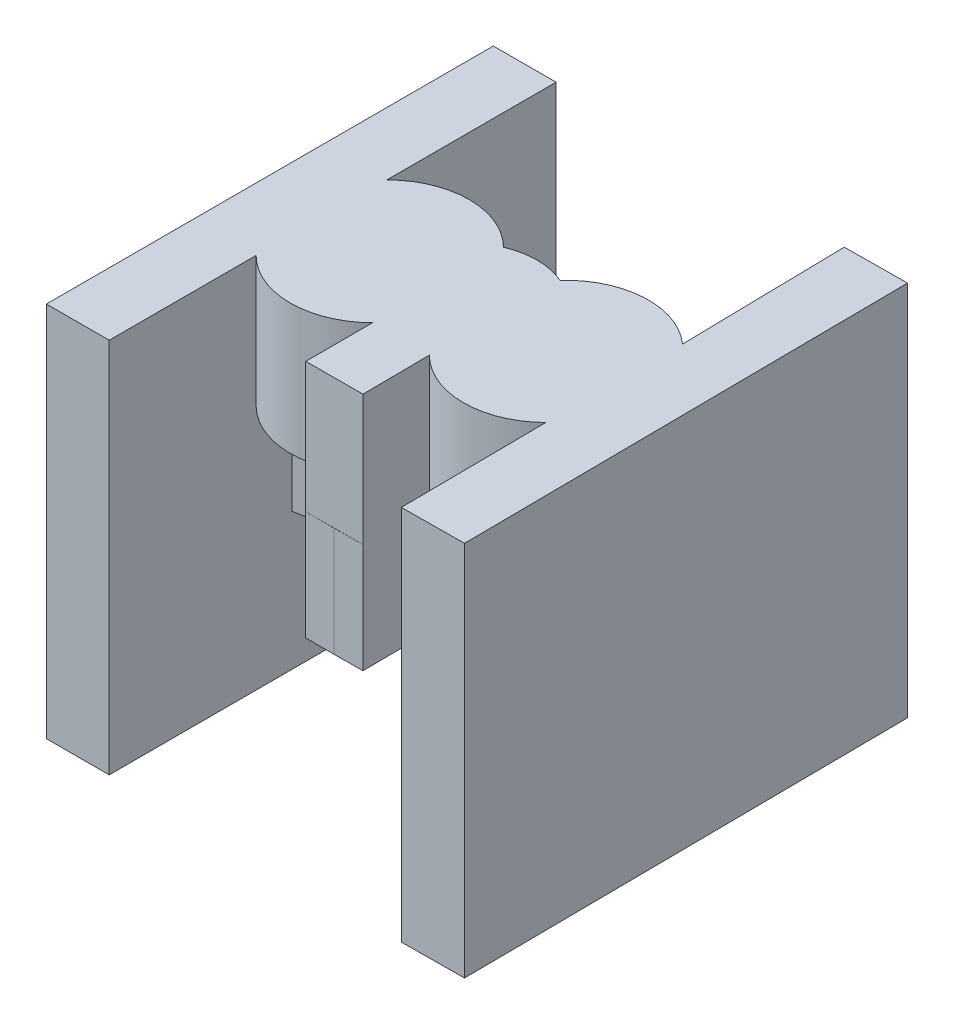
SolidWorks part; units mm, degrees
ref_plane "Front Plane" through (0, 0, 0) normal (0, 0, 1) x (1, 0, 0)
ref_plane "Top Plane" through (0, 0, 0) normal (0, 1, 0) x (1, 0, 0)
ref_plane "Right Plane" through (0, 0, 0) normal (1, 0, 0) x (0, 0, -1)
sketch "Sketch1" plane through (0, 0, 0) normal (0, 1, 0) x (1, 0, 0)
  line L0 (118.5, 375) -> (592.5, 375) construction
  line L1 (27.997, 26.1044) -> (30.497, 26.1044)
  line L2 (32.9969, 26.126) -> (30.497, 26.1044)
  line L3 (32.9969, 26.126) -> (32.9463, 31.9923)
  line L4 (43.0882, 40.7909) -> (40.3953, 39.9592)
  line L5 (42.9365, 58.3777) -> (43.0882, 40.7909)
  line L6 (48.4363, 58.4251) -> (42.9365, 58.3777)
  line L7 (48.7742, 19.251) -> (48.4363, 58.4251)
  line L8 (43.2744, 19.2036) -> (48.7742, 19.251)
  line L9 (43.1362, 35.2238) -> (43.2744, 19.2036)
  line L10 (40.4315, 35.7538) -> (43.1362, 35.2238)
  line L11 (24.9791, 40.7283) -> (20.4796, 39.8733)
  line L12 (25.0572, 34.5446) -> (20.4796, 35.6677)
  line L13 (20.4796, 35.6677) -> (17.7796, 35.1144)
  line L14 (17.7796, 35.1144) -> (17.7796, 19.0937)
  line L15 (17.7796, 19.0937) -> (12.2796, 19.0937)
  line L16 (12.2796, 19.0937) -> (12.2796, 58.2692)
  line L17 (12.2796, 58.2692) -> (17.7796, 58.2692)
  line L18 (17.7796, 58.2692) -> (17.7796, 40.6817)
  line L19 (17.7796, 40.6817) -> (20.4796, 39.8733)
  line L20 (35.8639, 34.5912) -> (40.4315, 35.7538)
  line L21 (27.997, 26.1044) -> (27.997, 31.971)
  line L22 (35.8886, 40.7754) -> (40.3953, 39.9592)
  arc A0 (25.0572, 34.5446) -> (27.997, 31.971) centre (30.4202, 37.7047) ccw
  arc A1 (30.4202, 43.9295) -> (24.9791, 40.7283) centre (30.4202, 37.7047) ccw
  arc A2 (30.4202, 43.9295) -> (35.8886, 40.7754) centre (30.4738, 37.7049) cw
  arc A3 (35.8639, 34.5912) -> (32.9463, 31.9923) centre (30.4738, 37.7049) cw
  dimension "D9" = 30.4202
  dimension "D2" = 6.2248
  dimension "D1" = 39.1755
  dimension "D3" = 12.2796
  dimension "D4" = 5.5
  dimension "D5" = 7.2775
  dimension "D6" = 19.0937
  dimension "D7" = 27.997
  dimension "D8" = 7.1994
  dimension "D10" = 30.497
  dimension "D11" = 4.2056
  dimension "D12" = 17.5875
  dimension "D13" = 16.0208
  dimension "D14" = 26.1044
  dimension "D15" = 31.971
  dimension "D16" = 30.4738
  dimension "D17" = 35.8639
  dimension "D18" = 2.7
  dimension "D19" = 2.7
  dimension "D20" = 35.8886
  dimension "D21" = 40.3953
  dimension "D22" = 40.4315
extrude "Boss-Extrude1" add sketch "Sketch1" along normal blind 33
sketch "Sketch2" plane through (0, 0, 0) normal (0, -1, 0) x (1, 0, 0)
  line L0 (17.7796, -35.1144) -> (17.7796, -40.6817)
  line L1 (17.7796, -40.6817) -> (20.4796, -39.8733)
  line L2 (20.4796, -39.8733) -> (24.9791, -40.7283)
  line L4 (25.0572, -34.5446) -> (20.4796, -35.6677)
  line L5 (27.997, -31.971) -> (27.997, -26.1044)
  line L6 (27.997, -26.1044) -> (32.9969, -26.126)
  line L7 (32.9969, -26.126) -> (32.9463, -31.9923)
  line L8 (35.8639, -34.5912) -> (40.4315, -35.7538)
  line L9 (40.4315, -35.7538) -> (43.1362, -35.2238)
  line L10 (43.1362, -35.2238) -> (43.0882, -40.7909)
  line L11 (43.0882, -40.7909) -> (40.3953, -39.9592)
  line L12 (40.3953, -39.9592) -> (35.8886, -40.7754)
  arc A0 (25.0572, -34.5446) -> (27.997, -31.971) centre (30.4202, -37.7047) cw
  arc A1 (32.9463, -31.9923) -> (35.8639, -34.5912) centre (30.4738, -37.7049) cw
  arc A2 (24.9791, -40.7283) -> (30.4202, -43.9295) centre (30.4202, -37.7047) ccw
  arc A3 (30.4202, -43.9295) -> (35.8886, -40.7754) centre (30.4202, -37.6119) ccw
extrude "Cut-Extrude1" cut sketch "Sketch2" against normal blind 12 and the other way through all
sketch "Sketch3" plane through (0, 0, -26.1044) normal (0, 0, 1) x (1, 0, 0)
  line L0 (30.497, 33) -> (30.497, 0) construction
  line L1 (27.997, 12) -> (37.4782, 12)
  line L2 (27.997, 12) -> (27.997, -5.0217)
  line L3 (27.997, -5.0217) -> (37.4782, -5.0217)
  line L4 (37.4782, 12) -> (37.4782, -5.0217)
  line L5 (27.997, 33) -> (30.497, 33) construction
  dimension "D1" = 6.9812
  dimension "D2" = 38.0217
extrude "Cut-Extrude2" cut sketch "Sketch3" against normal blind 22
sketch "Sketch6" plane through (17.7796, 0, 0) normal (1, 0, 0) x (0, 0, -1)
  line L0 (58.2692, 33) -> (58.2692, 0) construction
  line L1 (19.0937, 33) -> (58.2692, 33)
  line L2 (19.0937, 33) -> (19.0937, 21.584)
  line L3 (19.0937, 21.584) -> (58.2692, 21.584)
  line L4 (58.2692, 33) -> (58.2692, 21.584)
  line L5 (19.0937, 0) -> (58.2692, 0) construction
  dimension "D1" = 17.5875
  dimension "D2" = 21.584
extrude "Boss-Extrude3" add sketch "Sketch6" along normal blind 26
sketch "Sketch7" plane through (0, 21.584, 0) normal (0, -1, 0) x (1, 0, 0)
  line L0 (17.7796, -19.0937) -> (17.7796, -35.1144) construction
  line L1 (43.1362, -35.2238) -> (43.2744, -19.2036) construction
  line L2 (17.7796, -40.6817) -> (17.7796, -58.2692) construction
  line L3 (32.9969, -26.126) -> (32.9463, -31.9923) construction
  line L4 (32.9463, -31.9923) -> (32.9969, -26.126)
  line L5 (32.9969, -26.126) -> (27.997, -26.1044)
  line L6 (27.997, -26.1044) -> (27.997, -31.971)
  line L7 (43.2053, -43.9297) -> (42.9374, -58.2692)
  line L8 (42.9374, -58.2692) -> (17.7796, -58.2692)
  line L9 (17.7796, -58.2692) -> (17.7796, -43.4385)
  line L10 (17.7796, -31.971) -> (17.7796, -19.0937)
  line L11 (17.7796, -19.0937) -> (43.2744, -19.0937)
  line L12 (43.7796, -19.0937) -> (17.7796, -19.0937) construction
  line L13 (43.2744, -19.0937) -> (43.7796, -19.0937)
  line L14 (43.7796, -19.0937) -> (43.7796, -19.208)
  line L15 (43.7796, -19.208) -> (43.2744, -19.2036)
  line L16 (43.2744, -19.2036) -> (43.1641, -31.9923)
  line L17 (43.7796, -19.0937) -> (43.7796, -19.208) construction
  arc A0 (27.997, -43.4385) -> (30.4202, -43.9295) centre (30.4762, -37.428) ccw
  arc A1 (30.4202, -43.9295) -> (32.9969, -43.3954) centre (30.4738, -37.7049) ccw
  arc A2 (27.997, -43.4385) -> (17.7796, -43.4385) centre (22.8883, -38.3298) cw
  arc A3 (24.9791, -40.7283) -> (30.4202, -43.9295) centre (30.4202, -37.7047) ccw construction
  arc A4 (32.9969, -43.3954) -> (43.2053, -43.9297) centre (38.3682, -38.5584) ccw
  arc A5 (30.4202, -43.9295) -> (35.8886, -40.7754) centre (30.4738, -37.7049) ccw construction
  arc A6 (32.9463, -31.9923) -> (43.1641, -31.9923) centre (38.0552, -37.1012) cw
  arc A7 (35.8639, -34.5912) -> (32.9463, -31.9923) centre (30.4738, -37.7049) ccw construction
  arc A8 (27.997, -31.971) -> (17.7796, -31.971) centre (22.8883, -37.0796) ccw
  dimension "D1" = 6.5017
  dimension "D2" = 7.2248
  dimension "D3" = 0.5744
  dimension "D4" = 7.2283
  dimension "D5" = 7.225
  dimension "D6" = 5.4114
extrude "Cut-Extrude3" cut sketch "Sketch7" against normal blind 26
